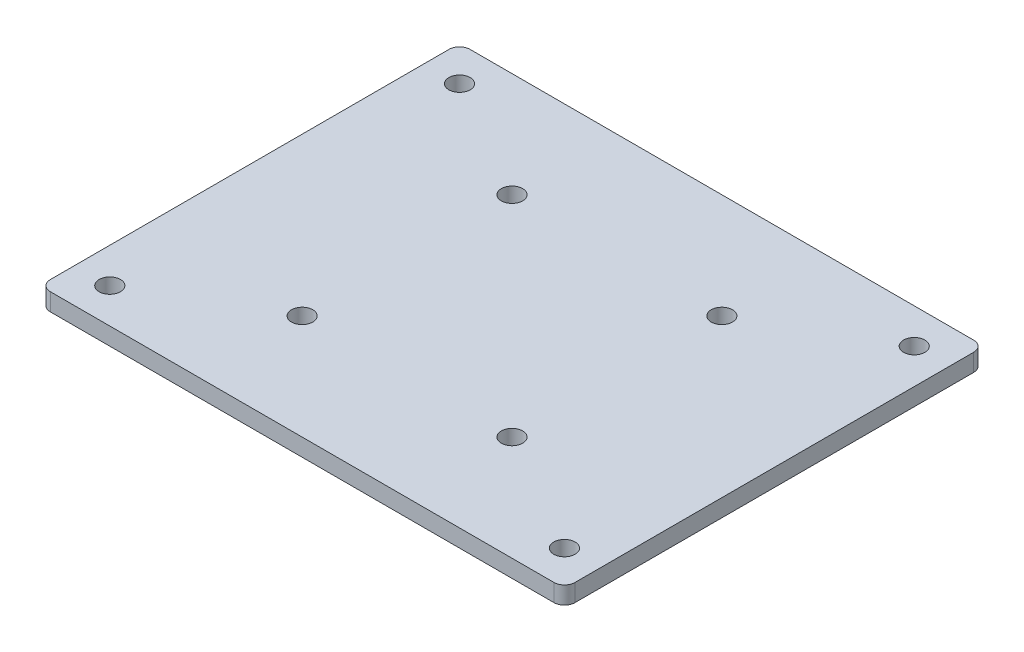
SolidWorks part; units mm, degrees
ref_plane "Front Plane" through (0, 0, 0) normal (0, 0, 1) x (1, 0, 0)
ref_plane "Top Plane" through (0, 0, 0) normal (0, 1, 0) x (1, 0, 0)
ref_plane "Right Plane" through (0, 0, 0) normal (1, 0, 0) x (0, 0, -1)
sketch "Sketch1" plane through (0, 0, 0) normal (0, 1, 0) x (1, 0, 0)
  line L1 (-75, 60) -> (75, 60)
  line L2 (-75, 60) -> (-75, -60)
  line L3 (-75, -60) -> (75, -60)
  line L4 (75, 60) -> (75, -60)
  line L5 (-75, 60) -> (75, -60) construction
  line L6 (-75, -60) -> (75, 60) construction
  point P0 (0, 0)
  dimension "D1" = 150
  dimension "D2" = 120
extrude "Boss-Extrude1" add sketch "Sketch1" along normal blind 5
sketch "Sketch2" plane through (0, 5, 0) normal (0, 1, 0) x (1, 0, 0)
  line L0 (75, 60) -> (-75, 60) construction
  line L1 (-75, 60) -> (-75, -60) construction
  line L2 (-75, -60) -> (75, -60) construction
  line L3 (75, -60) -> (75, 60) construction
  circle A0 centre (-30, 30) radius 3.05
  circle A1 centre (30, 30) radius 3.05
  circle A2 centre (30, -30) radius 3.05
  circle A3 centre (-30, -30) radius 3.05
  circle A4 centre (-65, 50) radius 3.05
  circle A5 centre (65, 50) radius 3.05
  circle A6 centre (-65, -50) radius 3.05
  circle A7 centre (65, -50) radius 3.05
  dimension "D1" = 6.1
  dimension "D2" = 45
  dimension "D3" = 30
  dimension "D4" = 30
  dimension "D5" = 45
  dimension "D6" = 45
  dimension "D7" = 30
  dimension "D8" = 45
  dimension "D10" = 6.1
  dimension "D11" = 10
  dimension "D12" = 10
  dimension "D13" = 10
  dimension "D14" = 10
extrude "Cut-Extrude1" cut sketch "Sketch2" against normal blind 10
fillet "Fillet1" radius 3 4 edges at (-75, 2.5, -60) (75, 2.5, -60) (75, 2.5, 60) (-75, 2.5, 60)
